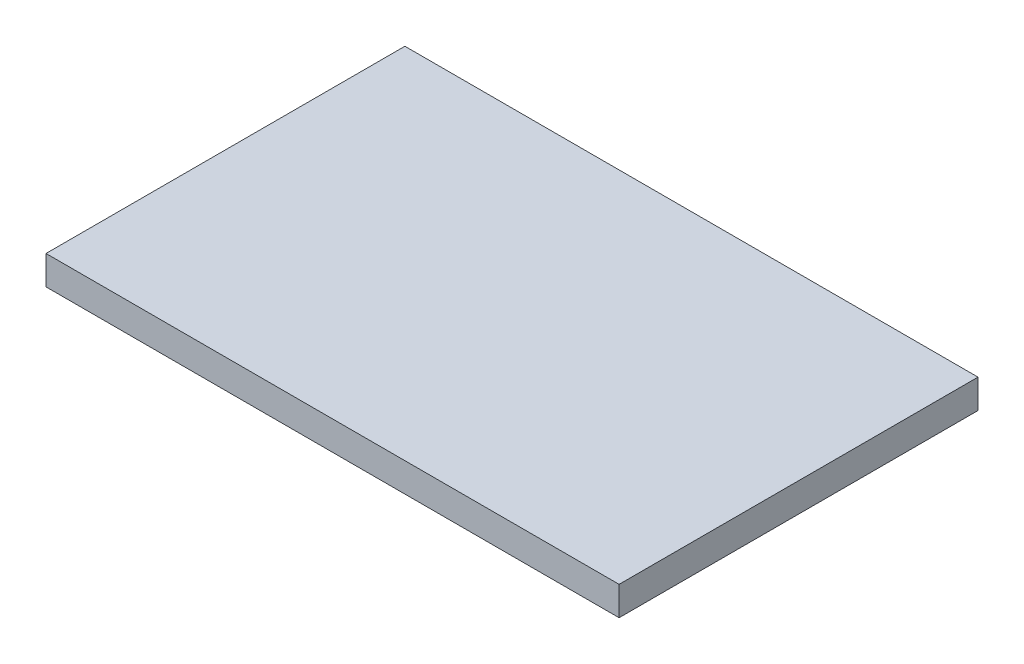
SolidWorks part; units mm, degrees
ref_plane "Спереди" through (0, 0, 0) normal (0, 0, 1) x (1, 0, 0)
ref_plane "Сверху" through (0, 0, 0) normal (0, 1, 0) x (1, 0, 0)
ref_plane "Справа" through (0, 0, 0) normal (1, 0, 0) x (0, 0, -1)
sketch "Эскиз2" plane through (0, 0, 0) normal (0, 1, 0) x (1, 0, 0)
  line L1 (-66.2043, 277.9364) -> (428.7957, 277.9364)
  line L2 (-66.2043, 277.9364) -> (-66.2043, -32.0636)
  line L3 (-66.2043, -32.0636) -> (428.7957, -32.0636)
  line L4 (428.7957, 277.9364) -> (428.7957, -32.0636)
extrude "Бобышка-Вытянуть2" add sketch "Эскиз2" along normal blind 25 contours L2 L1 L4 L3
